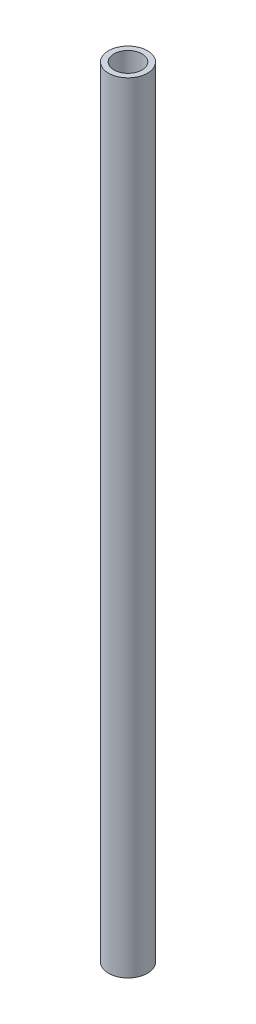
SolidWorks part; units mm, degrees
material "6061 Alloy"
ref_plane "Front Plane" through (0, 0, 0) normal (0, 0, 1) x (1, 0, 0)
ref_plane "Top Plane" through (0, 0, 0) normal (0, 1, 0) x (1, 0, 0)
ref_plane "Right Plane" through (0, 0, 0) normal (1, 0, 0) x (0, 0, -1)
sketch "Sketch1" plane through (0, 0, 0) normal (0, 1, 0) x (1, 0, 0)
  circle A0 centre (0, 0) radius 3.175
  circle A1 centre (0, 0) radius 2.286
  dimension "D1" = 6.35
  dimension "D2" = 0.889
extrude "Boss-Extrude1" add sketch "Sketch1" along normal blind 127
